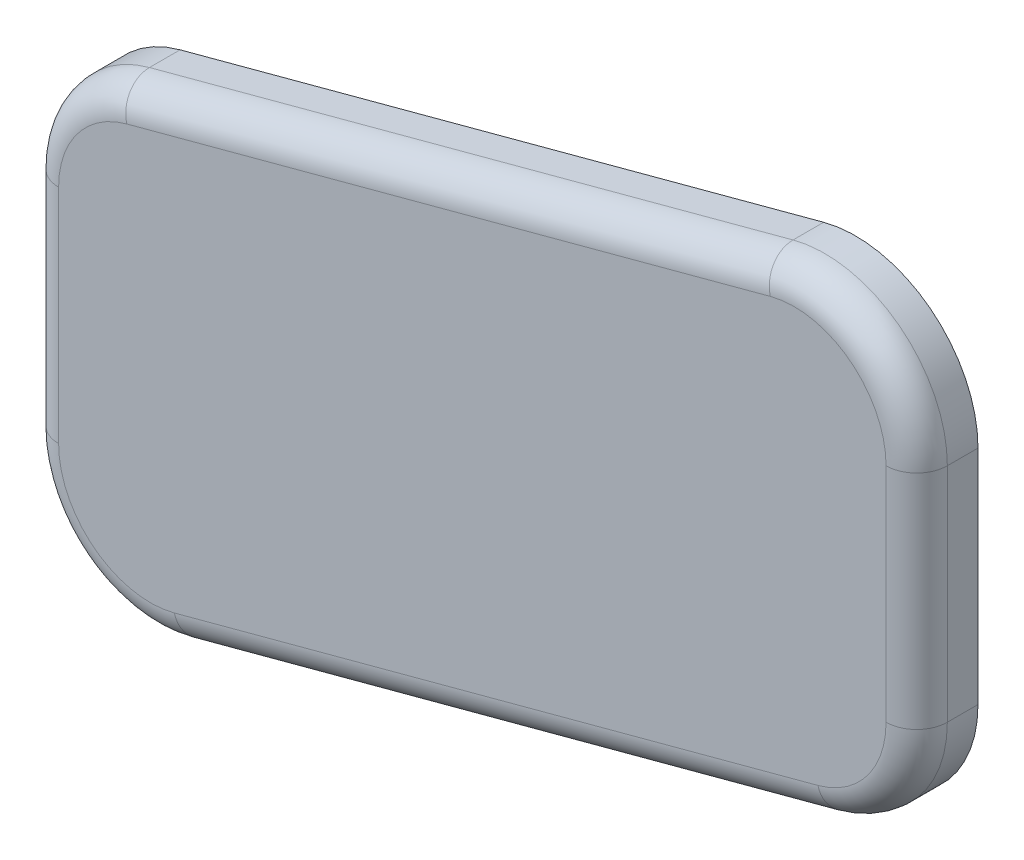
SolidWorks part; units mm, degrees
ref_plane "Спереди" through (0, 0, 0) normal (0, 0, 1) x (1, 0, 0)
ref_plane "Сверху" through (0, 0, 0) normal (0, 1, 0) x (1, 0, 0)
ref_plane "Справа" through (0, 0, 0) normal (1, 0, 0) x (0, 0, -1)
sketch "Эскиз1" plane through (0, 0, 0) normal (0, 0, 1) x (1, 0, 0)
  line L1 (0, 0) -> (29, 7.7705)
  line L2 (0, 0) -> (0, 15.5291)
  line L3 (0, 15.5291) -> (29, 23.2997)
  line L4 (29, 7.7705) -> (29, 23.2997)
  dimension "D1" = 75
  dimension "D2" = 29
  dimension "D3" = 15
extrude "Бобышка-Вытянуть1" add sketch "Эскиз1" along normal blind 2
fillet "Скругление1" radius 4 4 edges at (0, 15.5291, 1) (0, 0, 1) (29, 7.7705, 1) (29, 23.2997, 1)
fillet "Скругление2" radius 1 8 edges at (27.435, 21.2602, 2) (29, 14.4633, 2) (28.1734, 8.4048, 2) (15.5353, 4.1627, 2) (1.565, 2.0395, 2) (0, 8.8364, 2) (0.8266, 14.8949, 2) (13.4647, 19.137, 2)
